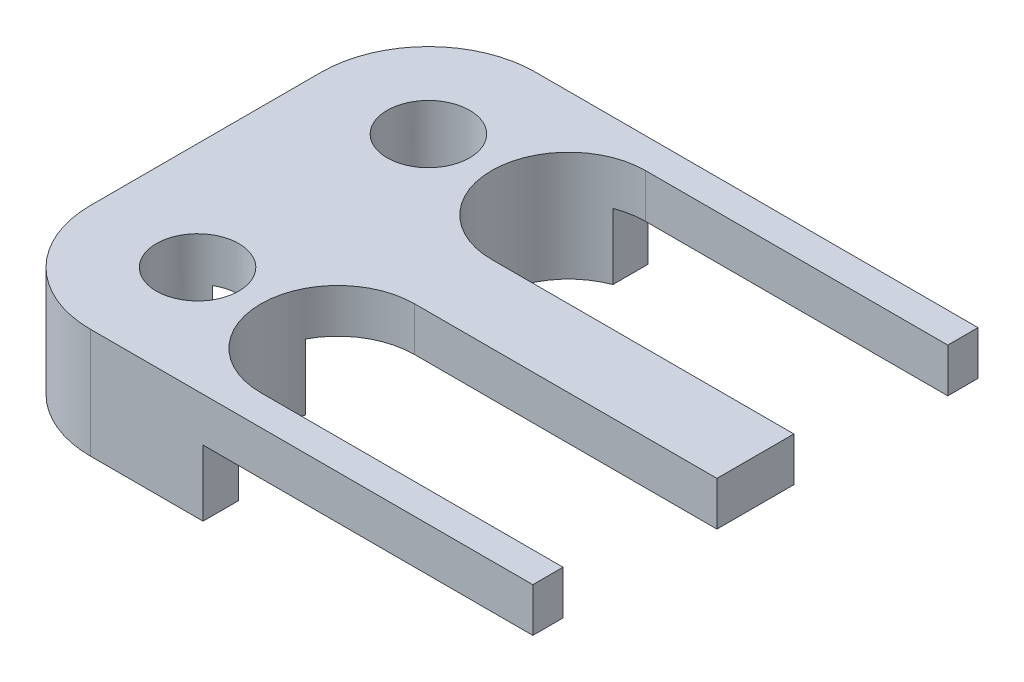
SolidWorks part; units mm, degrees
ref_plane "Alzado" through (0, 0, 0) normal (0, 0, 1) x (1, 0, 0)
ref_plane "Planta" through (0, 0, 0) normal (0, 1, 0) x (1, 0, 0)
ref_plane "Vista lateral" through (0, 0, 0) normal (1, 0, 0) x (0, 0, -1)
sketch "Croquis1" plane through (0, 0, 0) normal (0, 1, 0) x (1, 0, 0)
  line L0 (0, -10.5) -> (0, 10.5) construction
  line L1 (-9.75, -10.5) -> (-9.75, 10.5)
  line L2 (0, 20.25) -> (10.25, 20.25)
  line L4 (10.25, -20.25) -> (0, -20.25)
  line L5 (10.25, 20.25) -> (10.25, -20.25)
  circle A0 centre (0, 10.5) radius 3.75
  circle A1 centre (0, -10.5) radius 3.75
  arc A2 (-9.75, 10.5) -> (0, 20.25) centre (0, 10.5) cw
  arc A5 (0, -20.25) -> (-9.75, -10.5) centre (0, -10.5) cw
  point P2 (0, 0)
  dimension "D2" = 7.5
  dimension "D3" = 6
  dimension "D1" = 21
  dimension "D4" = 20
extrude "Saliente-Extruir1" add sketch "Croquis1" along normal blind 10
sketch "Croquis2" plane through (10.25, 0, 0) normal (1, 0, 0) x (0, 0, -1)
  line L0 (-20.25, 10) -> (20.25, 10)
  line L1 (-20.25, 10) -> (-20.25, 6)
  line L2 (20.25, 10) -> (20.25, 6)
  line L3 (-20.25, 6) -> (20.25, 6)
  dimension "D1" = 4
extrude "Saliente-Extruir2" add sketch "Croquis2" along normal blind 30
sketch "Croquis3" plane through (10.25, 0, 0) normal (1, 0, 0) x (0, 0, -1)
  line L0 (-20.25, 6) -> (20.25, 6) construction
  line L1 (-7.25, 0) -> (7.25, 0)
  line L2 (-7.25, 0) -> (-7.25, 6)
  line L3 (-7.25, 6) -> (7.25, 6)
  line L4 (7.25, 0) -> (7.25, 6)
  line L5 (-20.25, 0) -> (20.25, 0) construction
  point P4 (0, 0)
  point P7 (0, 0)
  point P10 (0, 6)
  dimension "D1" = 14.5
extrude "Cortar-Extruir1" cut sketch "Croquis3" against normal through all
sketch "Croquis5" plane through (0, 10, 0) normal (0, 1, 0) x (1, 0, 0)
  line L0 (0, 0) -> (40.25, 0) construction
  line L1 (40.25, 20.25) -> (40.25, -20.25) construction
  line L2 (12.75, -10.5) -> (40.25, -10.5) construction
  line L3 (12.75, -3.5) -> (40.25, -3.5)
  line L4 (12.75, -17.5) -> (40.25, -17.5)
  line L5 (0, -10.5) -> (3.75, -10.5) construction
  line L6 (12.75, 10.5) -> (40.25, 10.5) construction
  line L7 (12.75, 3.5) -> (40.25, 3.5)
  line L8 (12.75, 17.5) -> (40.25, 17.5)
  arc A0 (12.75, -3.5) -> (12.75, -17.5) centre (12.75, -10.5) ccw
  arc A1 (40.25, -17.5) -> (40.25, -3.5) centre (40.25, -10.5) ccw
  circle A2 centre (0, -10.5) radius 3.75 construction
  arc A3 (12.75, 3.5) -> (12.75, 17.5) centre (12.75, 10.5) cw
  arc A4 (40.25, 17.5) -> (40.25, 3.5) centre (40.25, 10.5) cw
  point P7 (26.5, -10.5)
  point P19 (26.5, 10.5)
  dimension "D1" = 14
  dimension "D2" = 9
extrude "Cortar-Extruir2" cut sketch "Croquis5" against normal through all
